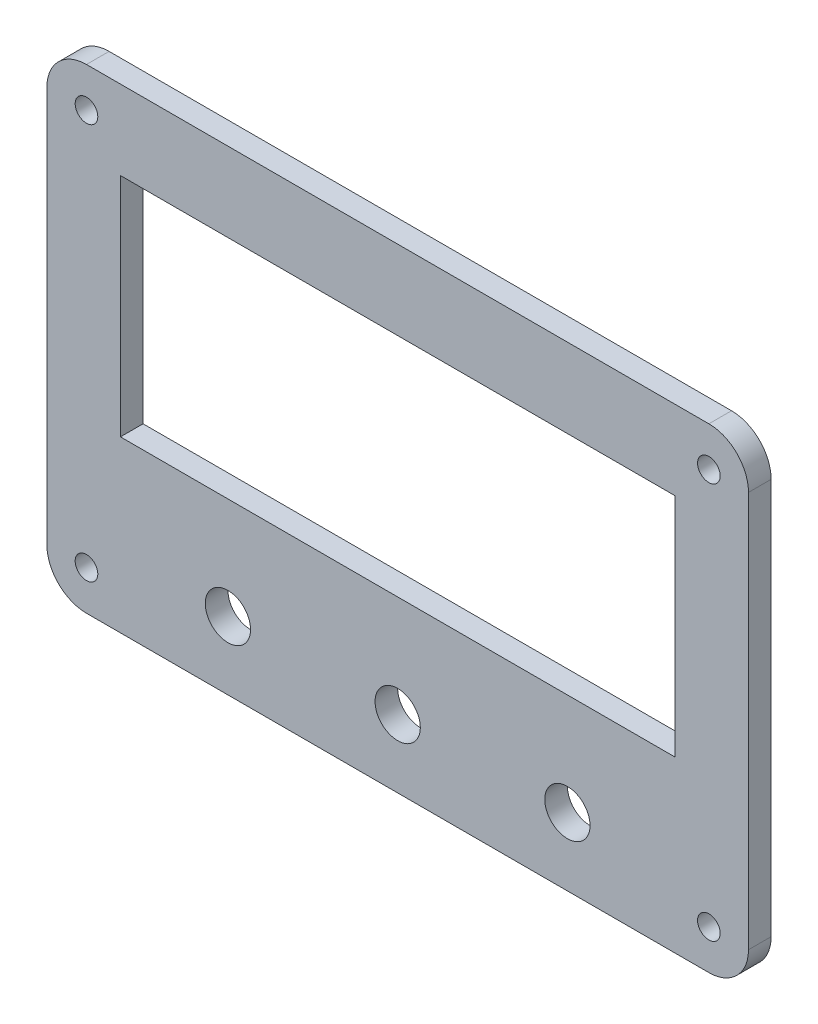
SolidWorks part; units mm, degrees
ref_plane "Alzado" through (0, 0, 0) normal (0, 0, 1) x (1, 0, 0)
ref_plane "Planta" through (0, 0, 0) normal (0, 1, 0) x (1, 0, 0)
ref_plane "Vista lateral" through (0, 0, 0) normal (1, 0, 0) x (0, 0, -1)
sketch "Croquis1" plane through (0, 0, 0) normal (0, 0, 1) x (1, 0, 0)
  line L0 (0, 0) -> (124, 0)
  line L1 (124, 0) -> (124, 84)
  line L3 (0, 84) -> (0, 0)
  line L4 (0, 84) -> (124, 84)
  line L8 (13, 70) -> (111, 70)
  line L10 (111, 70) -> (111, 30)
  line L14 (111, 30) -> (13, 30)
  line L15 (13, 30) -> (13, 70)
  circle A0 centre (7, 77) radius 2
  circle A1 centre (117, 77) radius 2
  circle A2 centre (117, 7) radius 2
  circle A3 centre (7, 7) radius 2
  circle A4 centre (32, 12) radius 4
  circle A5 centre (62, 12) radius 4
  circle A6 centre (92, 12) radius 4
  point P11 (0, 0)
  point P15 (0, 0)
extrude "Saliente-Extruir1" add sketch "Croquis1" along normal blind 4
fillet "Redondeo1" radius 7 4 edges at (0, 0, 2) (124, 0, 2) (124, 84, 2) (0, 84, 2)
